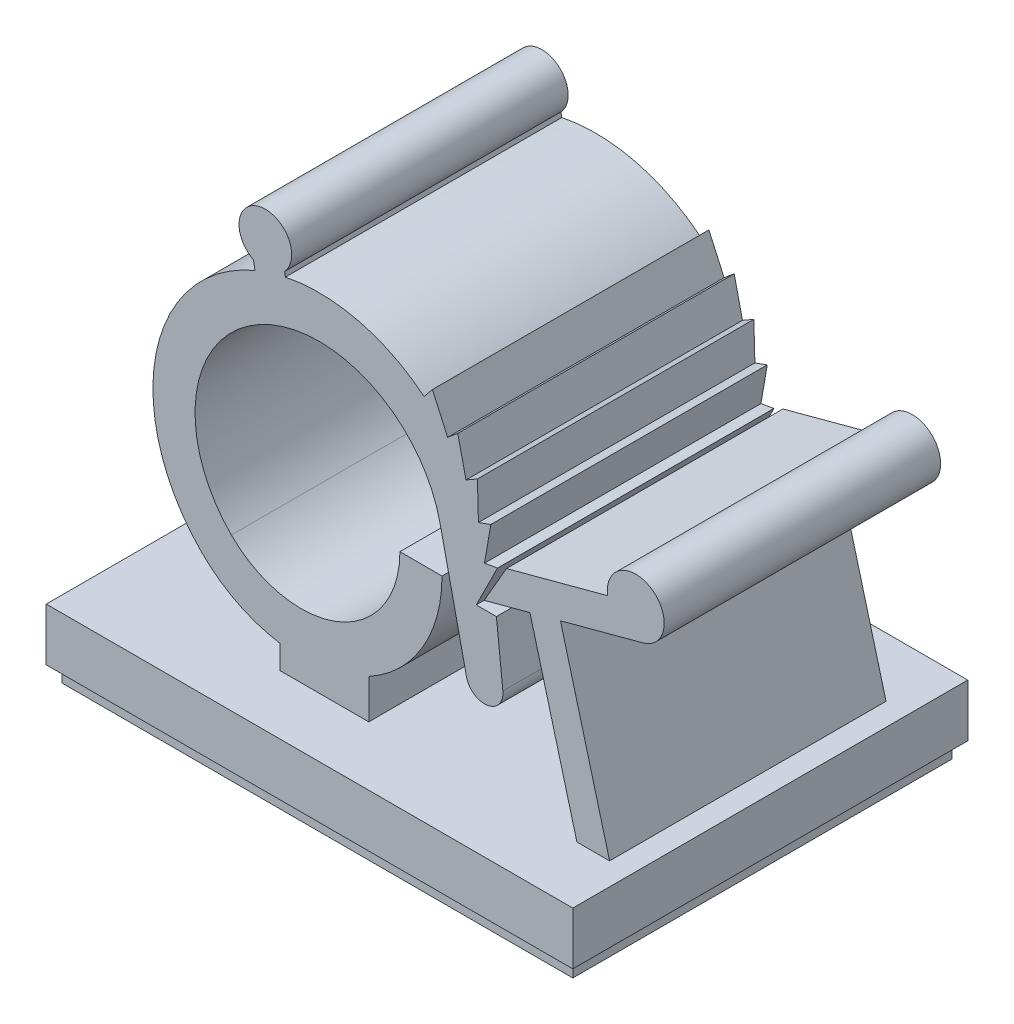
SolidWorks part; units mm, degrees
ref_plane "Front Plane" through (0, 0, 0) normal (0, 0, 1) x (1, 0, 0)
ref_plane "Top Plane" through (0, 0, 0) normal (0, 1, 0) x (1, 0, 0)
ref_plane "Right Plane" through (0, 0, 0) normal (1, 0, 0) x (0, 0, -1)
sketch "Sketch1" plane through (0, 0, 0) normal (0, 1, 0) x (1, 0, 0)
  line L1 (-12.7, -9.525) -> (12.7, -9.525)
  line L2 (-12.7, -9.525) -> (-12.7, 9.525)
  line L3 (-12.7, 9.525) -> (12.7, 9.525)
  line L4 (12.7, -9.525) -> (12.7, 9.525)
  line L5 (-12.7, -9.525) -> (12.7, 9.525) construction
  line L6 (-12.7, 9.525) -> (12.7, -9.525) construction
  point P0 (0, 0)
  dimension "Length" = 25.4
  dimension "Width" = 19.05
extrude "Boss-Extrude1" add sketch "Sketch1" along normal blind 2.54 from offset 0.762
sketch "Sketch2" plane through (0, 0.762, 0) normal (0, -1, 0) x (1, 0, 0)
  line L8 (12.319, -9.144) -> (12.319, 9.144)
  line L9 (12.319, 9.144) -> (-12.319, 9.144)
  line L10 (-12.319, 9.144) -> (-12.319, -9.144)
  line L11 (-12.319, -9.144) -> (12.319, -9.144)
  line L12 (12.319, -9.144) -> (12.319, 9.144)
  line L13 (12.319, 9.144) -> (-12.319, 9.144)
  line L14 (-12.319, 9.144) -> (-12.319, -9.144)
  line L15 (-12.319, -9.144) -> (12.319, -9.144)
  dimension "D1" = 0.381
extrude "Boss-Extrude2" add sketch "Sketch2" along normal blind 0.762
sketch "Sketch3" plane through (0, 0, 0) normal (0, 0, 1) x (1, 0, 0)
  line L0 (12.7, 3.302) -> (-12.7, 3.302) construction
  line L1 (0, 5.2008) -> (0, 3.302) construction
  line L2 (-4.2862, 4.445) -> (-4.2862, 3.302) construction
  line L3 (0, 3.302) -> (-4.2862, 3.302) construction
  line L4 (-3.2608, 11.1617) -> (3.5337, 11.1617) construction
  line L5 (10.0383, 3.302) -> (7.7738, 11.7533)
  line L6 (10.0383, 3.302) -> (11.6161, 3.302)
  line L7 (-12.7, 3.302) -> (12.7, 3.302) construction
  line L8 (11.6161, 3.302) -> (9.2459, 12.1478)
  line L9 (9.2459, 12.1478) -> (13.2327, 13.2161)
  line L11 (11.5216, 14.3353) -> (6.6433, 13.0282)
  line L12 (6.6433, 13.0282) -> (5.5657, 11.1617)
  line L13 (5.5657, 11.1617) -> (7.7738, 11.7533)
  line L14 (-4.2862, 4.445) -> (0, 4.445) construction
  line L15 (-4.2862, 4.445) -> (0, 5.2008) construction
  line L17 (12.7, 3.302) -> (12.7, 0.762) construction
  circle A0 centre (-3.2608, 11.1617) radius 4.7625 construction
  arc A1 (0, 5.2008) -> (-4.2862, 4.445) centre (-3.2608, 11.1617) ccw construction
  arc A2 (13.2327, 13.2161) -> (11.5216, 14.3353) centre (12.8777, 14.5409) ccw
  circle A3 centre (-3.2608, 11.1617) radius 6.7945 construction
  arc A4 (0.9752, 3.4181) -> (-4.5929, 2.4363) centre (-3.2608, 11.1617) ccw construction
  point P11 (10.0293, 16.8558)
  dimension "MBD" = 9.525
  dimension "D11" = 1.3716
  dimension "D2" = 4.2863
  dimension "D3" = 1.143
  dimension "D4" = 10
  dimension "D5" = 1.524
  dimension "D6" = 1.524
  dimension "D8" = 15
  dimension "D9" = 2.286
  dimension "D10" = 45
  dimension "D12" = 7.9375
  dimension "D1" = 2.032
  dimension "D7" = 2.032
sketch "Sketch4" plane through (0, 0, 0) normal (0, 0, 1) x (1, 0, 0)
  line L0 (1.5017, 11.1617) -> (3.5337, 11.1617)
  line L1 (0, 5.2008) -> (0, 3.302) construction
  line L2 (-4.2863, 4.445) -> (-4.2862, 3.302) construction
  line L3 (0, 5.2008) -> (0, 3.302)
  line L4 (-4.2863, 4.445) -> (-4.2862, 3.302)
  line L5 (-4.2862, 3.302) -> (0, 3.302)
  line L6 (-3.2608, 11.1617) -> (6.2091, 12.8315) construction
  line L7 (-3.2608, 11.1617) -> (3.5337, 11.1617) construction
  line L8 (-3.2608, 11.1617) -> (5.8872, 14.4913) construction
  line L9 (-3.2608, 11.1617) -> (5.2412, 16.0703) construction
  line L10 (-3.2608, 11.1617) -> (-8.0653, 6.3572) construction
  line L11 (-3.2608, 11.1617) -> (-3.2608, 19.9882) construction
  line L12 (3.5337, 11.1617) -> (5.5657, 11.1617) construction
  line L13 (-3.2608, 11.1617) -> (4.2918, 17.499) construction
  line L14 (5.1847, 11.1617) -> (5.1847, 10.7807) construction
  line L15 (5.1847, 11.1617) -> (5.5657, 11.1617) construction
  line L16 (5.1847, 10.7807) -> (6.2091, 12.8315)
  line L17 (-3.2608, 11.1617) -> (-4.9877, 20.955) construction
  line L18 (6.2091, 12.8315) -> (5.5816, 12.7208)
  line L19 (5.5816, 12.7208) -> (5.8872, 14.4913)
  line L20 (5.8872, 14.4913) -> (5.2893, 14.2737)
  line L21 (5.2893, 14.2737) -> (5.2412, 16.0703)
  line L22 (5.2412, 16.0703) -> (4.6908, 15.7526)
  line L23 (-3.2608, 11.1617) -> (2.6683, 18.2278) construction
  line L24 (4.6908, 15.7526) -> (4.2918, 17.499)
  line L25 (4.2918, 17.499) -> (3.8053, 17.0908)
  line L26 (3.8053, 17.0908) -> (3.07, 18.7196)
  line L27 (3.07, 18.7196) -> (2.6683, 18.2278)
  line L28 (5.1847, 10.7807) -> (6.1574, 10.7807)
  line L29 (6.1574, 10.7807) -> (6.4672, 7.8254)
  line L30 (3.4391, 13.3132) -> (4.715, 7.5408)
  line L31 (3.5337, 11.1617) -> (3.9147, 11.1617) construction
  line L32 (-5.4898, 19.4148) -> (-5.5616, 19.8221)
  line L33 (-4.0223, 19.8686) -> (-4.0608, 20.0868)
  line L34 (-5.7381, 20.8227) -> (-4.2372, 21.0873) construction
  line L36 (12.319, 0) -> (-12.319, 0) construction
  circle A0 centre (-3.2608, 11.1617) radius 4.7625 construction
  arc A1 (0, 5.2008) -> (-4.2863, 4.445) centre (-3.2608, 11.1617) ccw construction
  arc A2 (-6.6284, 7.7941) -> (1.5017, 11.1617) centre (-3.2608, 11.1617) ccw
  arc A3 (0, 5.2008) -> (3.5337, 11.1617) centre (-3.2608, 11.1617) ccw
  arc A4 (6.197, 11.0934) -> (3.07, 18.7196) centre (-2.3999, 12.0226) ccw construction
  arc A5 (-8.0653, 6.3572) -> (-4.2863, 4.445) centre (-3.2608, 11.1617) ccw
  arc A6 (-6.6284, 7.7941) -> (3.4391, 13.3132) centre (-2.3999, 12.0226) cw
  arc A7 (-8.0653, 6.3572) -> (-5.4898, 19.4148) centre (-2.3999, 12.0226) cw
  arc A8 (5.5657, 11.1617) -> (2.6683, 18.2278) centre (-2.3999, 12.0226) ccw construction
  arc A9 (0.9752, 3.4181) -> (-4.5929, 2.4363) centre (-3.2608, 11.1617) ccw construction
  arc A10 (4.715, 7.5408) -> (6.4672, 7.8254) centre (5.583, 7.7327) ccw
  arc A11 (-4.0223, 19.8686) -> (2.6683, 18.2278) centre (-2.3999, 12.0226) cw
  arc A12 (-4.0608, 20.0868) -> (-5.5616, 19.8221) centre (-4.9877, 20.955) ccw
  point P28 (4.2918, 17.499)
  point P37 (2.6683, 18.2278)
  dimension "D4" = 10
  dimension "D9" = 0.889
  dimension "D13" = 1.27
  dimension "D2" = 45
  dimension "D5" = 40
  dimension "D3" = 10
  dimension "D6" = 10
  dimension "D7" = 10
  dimension "D8" = 0.381
  dimension "D10" = 3.048
  dimension "D11" = 10
  dimension "D12" = 1.524
  dimension "Height" = 22.225
  dimension "D1" = 0.635
extrude "Boss-Extrude3" add sketch "Sketch4" along normal mid plane 13.335
extrude "Boss-Extrude4" add sketch "Sketch3" along normal mid plane 13.335
equation "\"D2@Sketch3\"=\"MBD@Sketch3\"*.450"
equation "\"D7@Sketch3\"=\"D1@Sketch3\""
equation "\"D6@Sketch3\"=\"D5@Sketch3\""
equation "\"D11@Sketch3\"=\"D6@Sketch3\"*.9"
equation "\"D1@Boss-Extrude3\"=\"Width@Sketch1\"*.7"
equation "\"D1@Boss-Extrude4\"=\"D1@Boss-Extrude3\""
equation "\"D12@Sketch4\"=\"D5@Sketch3\""
